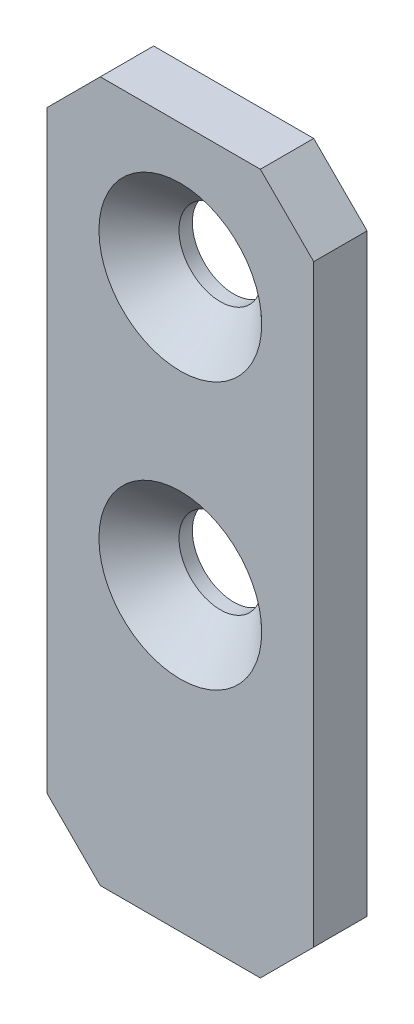
SolidWorks part; units mm, degrees
ref_plane "前视基准面" through (0, 0, 0) normal (0, 0, 1) x (1, 0, 0)
ref_plane "上视基准面" through (0, 0, 0) normal (0, 1, 0) x (1, 0, 0)
ref_plane "右视基准面" through (0, 0, 0) normal (1, 0, 0) x (0, 0, -1)
sketch "草图1" plane through (0, 0, 0) normal (0, 0, 1) x (1, 0, 0)
  line L1 (10, -26.25) -> (-10, -26.25)
  line L2 (10, -26.25) -> (10, 26.25)
  line L3 (10, 26.25) -> (-10, 26.25)
  line L4 (-10, -26.25) -> (-10, 26.25)
  line L5 (10, -26.25) -> (-10, 26.25) construction
  line L6 (10, 26.25) -> (-10, -26.25) construction
  circle A0 centre (0, 16.25) radius 3.1
  circle A1 centre (0, -3.75) radius 3.1
  point P0 (0, 0)
  dimension "D3" = 10
  dimension "D4" = 20
  dimension "D5" = 6.2
  dimension "D1" = 20
  dimension "D2" = 52.5
extrude "凸台-拉伸1" add sketch "草图1" along normal mid plane 4
chamfer "倒角1" distance 4 angle 45 4 edges at (-10, 26.25, 0) (10, 26.25, 0) (10, -26.25, 0) (-10, -26.25, 0)
chamfer "倒角2" distance 3 angle 45 2 edges at (3.1, 16.25, 2) (3.1, -3.75, 2)
